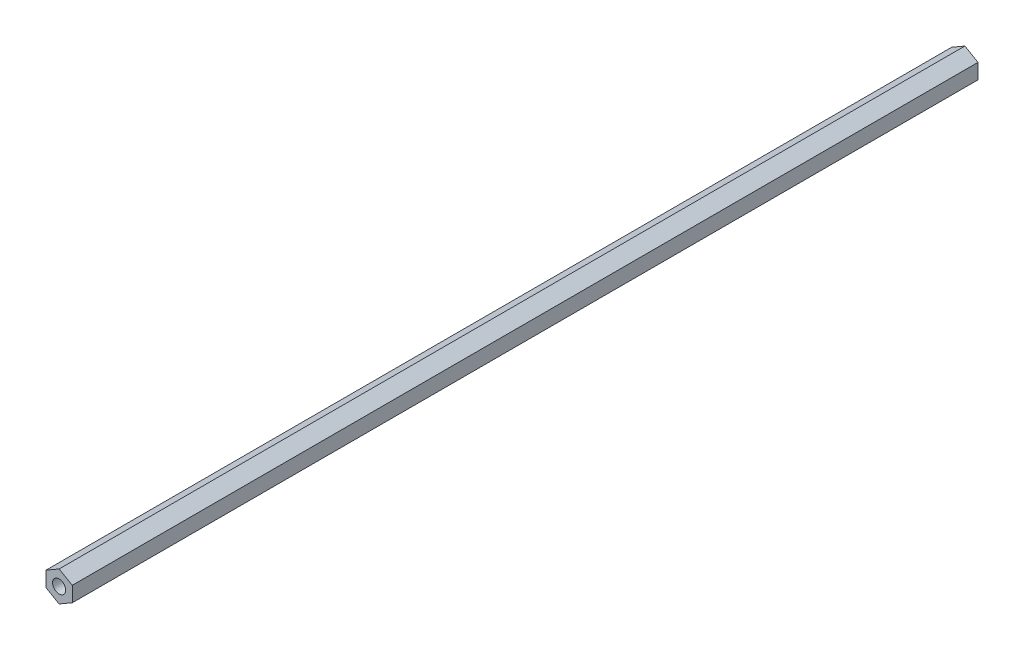
SolidWorks part; units mm, degrees
material "AISI 1020 Steel, Cold Rolled"
ref_plane "Front Plane" through (0, 0, 0) normal (0, 0, 1) x (1, 0, 0)
ref_plane "Top Plane" through (0, 0, 0) normal (0, 1, 0) x (1, 0, 0)
ref_plane "Right Plane" through (0, 0, 0) normal (1, 0, 0) x (0, 0, -1)
sketch "Sketch1" plane through (0, 0, 0) normal (0, 0, 1) x (1, 0, 0)
  line L1 (0, 7.3323) -> (-6.35, 3.6662) construction
  line L2 (-6.35, 3.6662) -> (-6.35, -3.6662) construction
  line L3 (-6.35, -3.6662) -> (0, -7.3323) construction
  line L4 (0, -7.3323) -> (6.35, -3.6662) construction
  line L5 (6.35, -3.6662) -> (6.35, 3.6662) construction
  line L6 (6.35, 3.6662) -> (0, 7.3323) construction
  circle A2 centre (0, 0) radius 6.35 construction
  dimension "Width" = 12.7
sketch "Sketch2" plane through (0, 0, 0) normal (1, 0, 0) x (0, 0, -1)
  line L0 (-219.075, 7.3323) -> (219.075, 7.3323) construction
  point P2 (0, 7.3323)
  point P3 (187.325, 7.3323)
  point P4 (-187.325, 7.3323)
  dimension "Length" = 438.15
  dimension "D2" = 31.75
  dimension "D1" = 31.75
sketch "Sketch3" plane through (0, 0, 0) normal (0, 0, 1) x (1, 0, 0)
  line L0 (-6.35, -3.6662) -> (0, -7.3323) construction
  line L1 (0, -7.3323) -> (6.35, -3.6662) construction
  line L2 (6.35, -3.6662) -> (6.35, 3.6662) construction
  line L3 (6.35, 3.6662) -> (0, 7.3323) construction
  line L4 (0, 7.3323) -> (-6.35, 3.6662) construction
  line L5 (-6.35, 3.6662) -> (-6.35, -3.6662) construction
  line L6 (-6.35, -3.6662) -> (0, -7.3323)
  line L7 (0, -7.3323) -> (6.35, -3.6662)
  line L8 (6.35, -3.6662) -> (6.35, 3.6662)
  line L9 (6.35, 3.6662) -> (0, 7.3323)
  line L10 (0, 7.3323) -> (-6.35, 3.6662)
  line L11 (-6.35, 3.6662) -> (-6.35, -3.6662)
extrude "Boss-Extrude2" add sketch "Sketch3" along normal up to vertex (219.075 mm away) and the other way up to vertex (219.075 mm away) up to point (0, 7.3323, 219.075) other way up to point (0, 7.3323, -219.075)
sketch "Sketch4" plane through (0, 0, 219.075) normal (0, 0, 1) x (1, 0, 0)
  point P0 (0, 0)
hole_wizard "1/4 (0.25) Diameter Hole1" positions "Sketch5" profile "Sketch6" hole size "1/4" standard "ANSI Inch"
sketch "Sketch5" plane through (0, 0, 219.075) normal (0, 0, 1) x (1, 0, 0)
  point P0 (0, 0)
sketch "Sketch6" plane through (0, 0, 219.075) normal (1, 0, 0) x (0, -1, 0)
  line L0 (0, 0) -> (0, 27.3077)
  line L1 (0, 27.3077) -> (3.175, 25.4)
  line L2 (3.175, 25.4) -> (3.175, 0)
  line L5 (3.175, 0) -> (0, 0)
  line L10 (0, 27.3077) -> (-3.175, 25.4) construction
  line L11 (0, -6.35) -> (0, 107.95) construction
  dimension "Hole Dia." = 6.35
  dimension "Hole Depth" = 25.4
  dimension "Drill Angle" = 118
hole_wizard "1/4 (0.25) Diameter Hole2" positions "Sketch7" profile "Sketch8" hole size "1/4" standard "ANSI Inch"
sketch "Sketch7" plane through (0, 0, -219.075) normal (0, 0, -1) x (-1, 0, 0)
  point P0 (0, 0)
sketch "Sketch8" plane through (0, 0, -219.075) normal (1, 0, 0) x (0, 1, 0)
  line L0 (0, 0) -> (0, 27.3077)
  line L1 (0, 27.3077) -> (3.175, 25.4)
  line L2 (3.175, 25.4) -> (3.175, 0)
  line L5 (3.175, 0) -> (0, 0)
  line L10 (0, 27.3077) -> (-3.175, 25.4) construction
  line L11 (0, -6.35) -> (0, 107.95) construction
  dimension "Hole Dia." = 6.35
  dimension "Hole Depth" = 25.4
  dimension "Drill Angle" = 118
equation "\"D2@Sketch2\" = \"D1@Sketch2\""
equation "\"D1@Sketch2\" = \"Width@Sketch1\" * 2.5"
